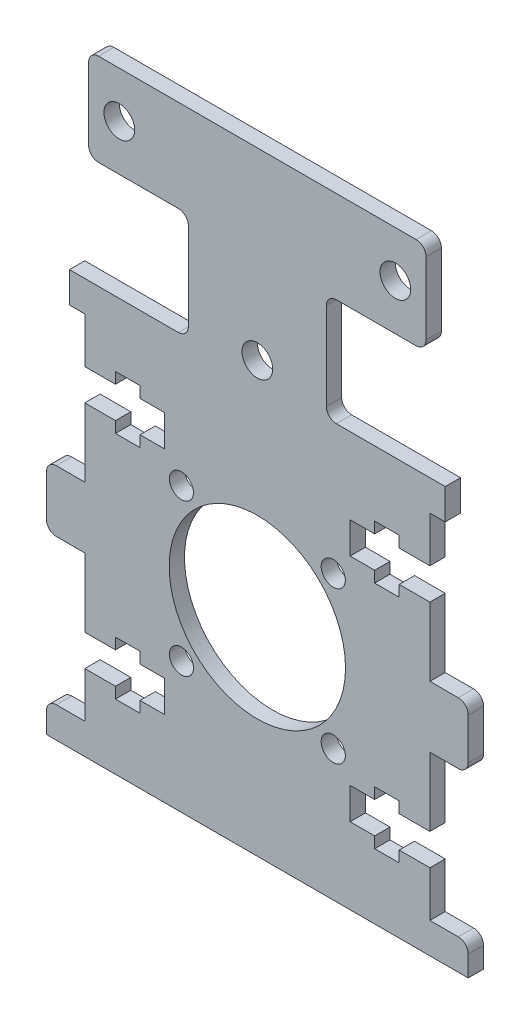
SolidWorks part; units mm, degrees
ref_plane "前视基准面" through (0, 0, 0) normal (0, 0, 1) x (1, 0, 0)
ref_plane "上视基准面" through (0, 0, 0) normal (0, 1, 0) x (1, 0, 0)
ref_plane "右视基准面" through (0, 0, 0) normal (1, 0, 0) x (0, 0, -1)
sketch "草图1" plane through (0, 0, 0) normal (0, 0, 1) x (1, 0, 0)
  line L0 (-22.5, 0) -> (-24.9483, 0) construction
  line L1 (22.5, -27) -> (-22.5, -27)
  line L3 (22.5, 27) -> (-22.5, 27) construction
  line L4 (-22.5, -27) -> (-22.5, 27) construction
  line L5 (22.5, -27) -> (-22.5, 27) construction
  line L6 (22.5, 27) -> (-22.5, -27) construction
  line L7 (-22.5, 4) -> (-27.5, 4)
  line L8 (-27.5, 4) -> (-27.5, -4)
  line L9 (-27.5, -4) -> (-22.5, -4)
  line L10 (-22.5, 17.05) -> (-18.5, 17.05)
  line L11 (-18.5, 17.05) -> (-18.5, 18.5)
  line L12 (-18.5, 18.5) -> (-15.3, 18.5)
  line L13 (-15.3, 18.5) -> (-15.3, 17.05)
  line L14 (-15.3, 17.05) -> (-12.1, 17.05)
  line L15 (-12.1, 17.05) -> (-12.1, 12.95)
  line L16 (-12.1, 12.95) -> (-15.3, 12.95)
  line L17 (-15.3, 12.95) -> (-15.3, 11.5)
  line L18 (-15.3, 11.5) -> (-18.5, 11.5)
  line L19 (-18.5, 11.5) -> (-18.5, 12.95)
  line L20 (-18.5, 12.95) -> (-22.5, 12.95)
  line L21 (-18.5, -12.95) -> (-22.5, -12.95)
  line L22 (-18.5, -11.5) -> (-18.5, -12.95)
  line L23 (-15.3, -11.5) -> (-18.5, -11.5)
  line L24 (-15.3, -12.95) -> (-15.3, -11.5)
  line L25 (-12.1, -12.95) -> (-15.3, -12.95)
  line L26 (-12.1, -17.05) -> (-12.1, -12.95)
  line L27 (-15.3, -17.05) -> (-12.1, -17.05)
  line L28 (-15.3, -18.5) -> (-15.3, -17.05)
  line L29 (-18.5, -18.5) -> (-15.3, -18.5)
  line L30 (-18.5, -17.05) -> (-18.5, -18.5)
  line L31 (-22.5, -17.05) -> (-18.5, -17.05)
  line L32 (-22.5, -23) -> (-27.5, -23)
  line L33 (-27.5, -23) -> (-27.5, -27)
  line L34 (-27.5, -27) -> (-22.5, -27)
  line L35 (-27.5, 23) -> (-27.5, 27)
  line L36 (-22.5, 23) -> (-27.5, 23)
  line L37 (-27.5, 27) -> (-22.5, 27)
  line L38 (0, 0) -> (0, -4) construction
  line L39 (22.5, -27) -> (22.5, 27) construction
  line L40 (22.5, 0) -> (24.9483, 0) construction
  line L41 (27.5, 27) -> (22.5, 27)
  line L42 (22.5, 23) -> (27.5, 23)
  line L43 (27.5, 23) -> (27.5, 27)
  line L44 (27.5, -27) -> (22.5, -27)
  line L45 (27.5, -23) -> (27.5, -27)
  line L46 (22.5, -23) -> (27.5, -23)
  line L47 (22.5, -17.05) -> (18.5, -17.05)
  line L48 (18.5, -17.05) -> (18.5, -18.5)
  line L49 (18.5, -18.5) -> (15.3, -18.5)
  line L50 (15.3, -18.5) -> (15.3, -17.05)
  line L51 (15.3, -17.05) -> (12.1, -17.05)
  line L52 (12.1, -17.05) -> (12.1, -12.95)
  line L53 (12.1, -12.95) -> (15.3, -12.95)
  line L54 (15.3, -12.95) -> (15.3, -11.5)
  line L55 (15.3, -11.5) -> (18.5, -11.5)
  line L56 (18.5, -11.5) -> (18.5, -12.95)
  line L57 (18.5, -12.95) -> (22.5, -12.95)
  line L58 (18.5, 12.95) -> (22.5, 12.95)
  line L59 (18.5, 11.5) -> (18.5, 12.95)
  line L60 (15.3, 11.5) -> (18.5, 11.5)
  line L61 (15.3, 12.95) -> (15.3, 11.5)
  line L62 (12.1, 12.95) -> (15.3, 12.95)
  line L63 (12.1, 17.05) -> (12.1, 12.95)
  line L64 (15.3, 17.05) -> (12.1, 17.05)
  line L65 (15.3, 18.5) -> (15.3, 17.05)
  line L66 (18.5, 18.5) -> (15.3, 18.5)
  line L67 (18.5, 17.05) -> (18.5, 18.5)
  line L68 (22.5, 17.05) -> (18.5, 17.05)
  line L69 (27.5, -4) -> (22.5, -4)
  line L70 (27.5, 4) -> (27.5, -4)
  line L71 (22.5, 4) -> (27.5, 4)
  line L72 (-22.5, 23) -> (-22.5, 17.05)
  line L73 (-22.5, 12.95) -> (-22.5, 4)
  line L74 (-22.5, -4) -> (-22.5, -12.95)
  line L75 (-22.5, -17.05) -> (-22.5, -23)
  line L76 (22.5, -23) -> (22.5, -17.05)
  line L77 (22.5, -12.95) -> (22.5, -4)
  line L78 (22.5, 4) -> (22.5, 12.95)
  line L79 (22.5, 23) -> (22.5, 17.05)
  line L80 (0, 0) -> (0, 47) construction
  line L81 (0, 47) -> (-18, 47) construction
  line L82 (22, 53) -> (-22, 53)
  line L83 (-22, 53) -> (-22, 41)
  line L84 (-22, 41) -> (-9, 41)
  line L85 (-9, 41) -> (-9, 27)
  line L86 (-9, 27) -> (-22.5, 27)
  line L87 (22, 53) -> (22, 41)
  line L88 (22, 41) -> (9, 41)
  line L89 (9, 41) -> (9, 27)
  line L90 (9, 27) -> (22.5, 27)
  line L91 (-12.1, 15) -> (-22.5, 15) construction
  circle A0 centre (0, 0) radius 14 construction
  circle A1 centre (9.8995, 9.8995) radius 1.575
  circle A5 centre (0, 0) radius 11.5
  circle A6 centre (9.8995, -9.8995) radius 1.575
  circle A7 centre (-9.8995, -9.8995) radius 1.575
  circle A8 centre (-9.8995, 9.8995) radius 1.575
  circle A9 centre (-18, 47) radius 2
  circle A10 centre (18, 47) radius 2
  circle A11 centre (0, 29) radius 2
  point P35 (-16.9, 11.5)
  point P48 (-21.5, -15)
  point P91 (21.5, -15)
  dimension "D2" = 23
  dimension "D12" = 3.15
  dimension "D17" = 28
  dimension "D21" = 18
  dimension "D22" = 18
  dimension "D27" = 4
  dimension "D3" = 45
  dimension "D4" = 54
  dimension "D5" = 8
  dimension "D6" = 5
  dimension "D7" = 4
  dimension "D8" = 15
  dimension "D9" = 3.2
  dimension "D10" = 4
  dimension "D11" = 4.1
  dimension "D13" = 7
  dimension "D14" = 4
  dimension "D15" = 5
  dimension "D19" = 29
  dimension "D20" = 18
  dimension "D23" = 13
  dimension "D24" = 12
  dimension "D25" = 6
  dimension "D26" = 4
  dimension "D18" = 4
extrude "凸台-拉伸1" add sketch "草图1" along normal blind 2
sketch "草图2" plane through (-22.5, 0, 0) normal (-1, 0, 0) x (0, 0, 1)
  line L0 (1, 17.05) -> (1, 12.95) construction
  line L1 (2, 17.05) -> (0, 17.05) construction
  line L2 (2, 12.95) -> (0, 12.95) construction
  line L3 (-0.15, 27.15) -> (4.15, 27.15) construction
  line L4 (4.15, -4.15) -> (-0.15, -4.15)
  line L5 (4.15, -4.15) -> (4.15, 4.15)
  line L6 (4.15, 4.15) -> (-0.15, 4.15)
  line L7 (-0.15, -4.15) -> (-0.15, 4.15)
  line L8 (4.15, -4.15) -> (-0.15, 4.15) construction
  line L9 (4.15, 4.15) -> (-0.15, -4.15) construction
  line L18 (4.15, 27.15) -> (4.15, 22.85)
  line L19 (-0.15, 22.85) -> (4.15, 22.85)
  line L20 (-0.15, 27.15) -> (-0.15, 22.85)
  line L21 (2, 0) -> (2.8697, 0) construction
  line L22 (-0.15, -27.15) -> (4.15, -27.15) construction
  line L23 (1, -17.05) -> (1, -12.95) construction
  line L24 (-0.15, -27.15) -> (-0.15, -22.85)
  line L25 (-0.15, -22.85) -> (4.15, -22.85)
  line L26 (4.15, -27.15) -> (4.15, -22.85)
  line L27 (4.15, -27.15) -> (8, -27.15)
  line L28 (8, -27.15) -> (8, 27.15)
  line L29 (8, 27.15) -> (4.15, 27.15)
  line L30 (-0.15, -27.15) -> (-64.002, -27.15)
  line L31 (-64.002, -27.15) -> (-64.002, 27.15)
  line L32 (-64.002, 27.15) -> (-0.15, 27.15)
  circle A0 centre (1, 15) radius 2.05
  circle A1 centre (1, -15) radius 2.05
  point P8 (2, 0)
  dimension "D1" = 8.3
  dimension "D2" = 4.3
sketch "草图3" plane through (22.5, 0, 0) normal (1, 0, 0) x (0, 0, -1)
  line L0 (-1, 12.95) -> (-1, 17.05)
  line L1 (-2, 12.95) -> (0, 12.95) construction
  line L2 (-2, 17.05) -> (0, 17.05) construction
  circle A0 centre (-1, 15) radius 2.05
fillet "圆角1" radius 1.3 16 edges at (-9, 27, 1) (9, 27, 1) (9, 41, 1) (-9, 41, 1) (22, 53, 1) (22, 41, 1) (-22, 53, 1) (-22, 41, 1) (-27.5, -23, 1) (-27.5, 23, 1) (-27.5, 4, 1) (-27.5, -4, 1) (27.5, -23, 1) (27.5, 4, 1) (27.5, -4, 1) (27.5, 23, 1)
sketch "草图4" plane through (0, 0, 2) normal (0, 0, 1) x (1, 0, 0)
  line L11 (27.5, 27) -> (24.5, 27)
  line L12 (27.5, 27) -> (27.5, 21.1214)
  line L13 (27.5, 21.1214) -> (24.5, 21.1214)
  line L14 (24.5, 27) -> (24.5, 21.1214)
  line L15 (-27.5, 27) -> (-24.5, 27)
  line L16 (-27.5, 27) -> (-27.5, 15.6557)
  line L17 (-27.5, 15.6557) -> (-24.5, 15.6557)
  line L18 (-24.5, 27) -> (-24.5, 15.6557)
extrude "切除-拉伸1" cut sketch "草图4" against normal blind 2
